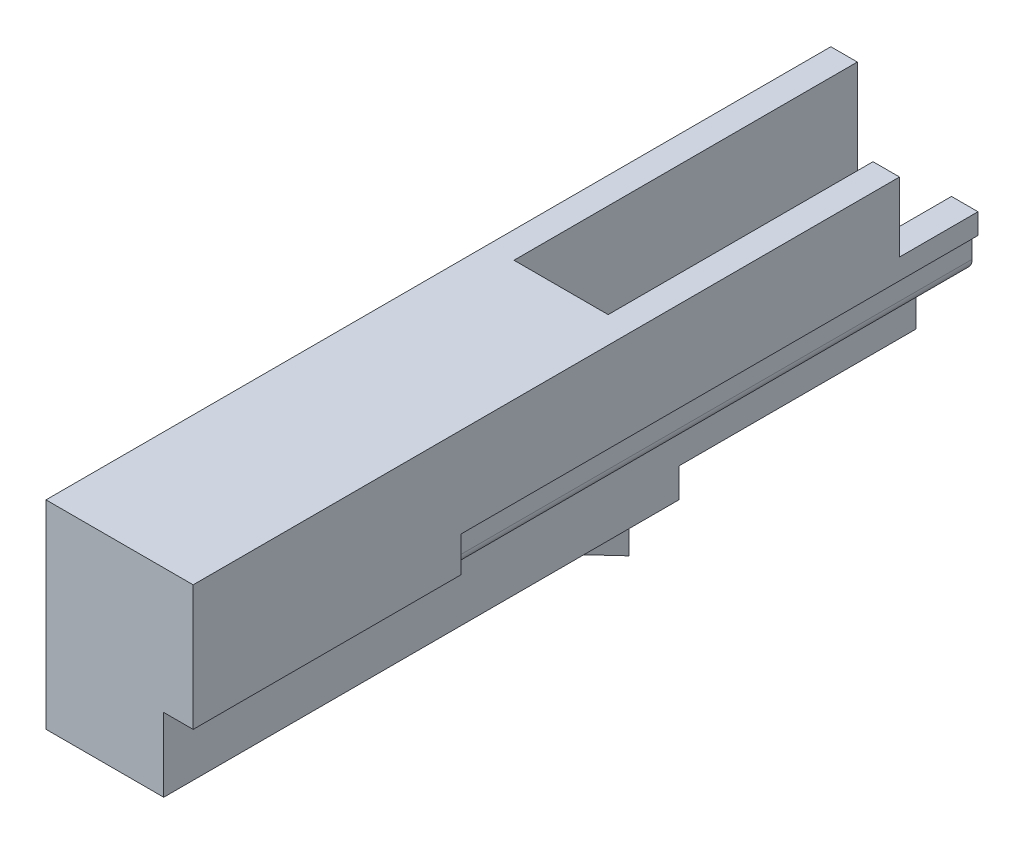
SolidWorks part; units mm, degrees
ref_plane "Front Plane" through (0, 0, 0) normal (0, 0, 1) x (1, 0, 0)
ref_plane "Top Plane" through (0, 0, 0) normal (0, 1, 0) x (1, 0, 0)
ref_plane "Right Plane" through (0, 0, 0) normal (1, 0, 0) x (0, 0, -1)
sketch "Sketch1" plane through (0, 0, 0) normal (0, 0, 1) x (1, 0, 0)
  line L0 (0, 0) -> (0, 86.52)
  line L1 (0, 86.52) -> (-50, 86.52)
  line L2 (-50, 86.52) -> (-50, 0)
  line L3 (-50, 0) -> (0, 0)
  dimension "D1" = 50
  dimension "D2" = 86.52
extrude "Boss-Extrude1" add sketch "Sketch1" along normal blind 266.658
sketch "Sketch2" plane through (0, 86.52, 0) normal (0, 1, 0) x (1, 0, 0)
  line L0 (-41, 0) -> (-41, -116.66)
  line L1 (0, 0) -> (-50, 0) construction
  line L2 (-41, -116.66) -> (-9, -116.66)
  line L3 (-9, -116.66) -> (-9, 0)
  line L4 (-9, 0) -> (-41, 0)
  line L5 (-50, -266.658) -> (-50, 0) construction
  dimension "D1" = 32
  dimension "D2" = 9
  dimension "D3" = 116.66
extrude "Cut-Extrude1" cut sketch "Sketch2" against normal blind 39.55
sketch "Sketch3" plane through (0, 46.97, 0) normal (0, 1, 0) x (1, 0, 0)
  line L0 (-41, 0) -> (-41, -11)
  line L1 (-41, 0) -> (-41, -116.66) construction
  line L2 (-41, -11) -> (-9, -11)
  line L3 (-9, -116.66) -> (-9, 0) construction
  line L4 (-9, -11) -> (-9, 0)
  line L5 (-9, 0) -> (-41, 0)
  dimension "D1" = 11
extrude "Cut-Extrude2" cut sketch "Sketch3" against normal through all
sketch "Sketch4" plane through (0, 46.97, 0) normal (0, 1, 0) x (1, 0, 0)
  line L0 (-36.5, -11) -> (-36.5, -44)
  line L1 (-41, -11) -> (-9, -11) construction
  line L2 (-36.5, -44) -> (-13.5, -44)
  line L3 (-13.5, -44) -> (-13.5, -11)
  line L4 (-13.5, -11) -> (-36.5, -11)
  line L5 (-41, -11) -> (-41, -116.66) construction
  dimension "D1" = 4.5
  dimension "D2" = 23
  dimension "D3" = 33
extrude "Cut-Extrude3" cut sketch "Sketch4" against normal through all
sketch "Sketch5" plane through (0, 46.97, 0) normal (0, 1, 0) x (1, 0, 0)
  line L0 (-34.5, -44) -> (-34.5, -96)
  line L1 (-36.5, -44) -> (-13.5, -44) construction
  line L2 (-34.5, -96) -> (-15.5, -96)
  line L3 (-15.5, -96) -> (-15.5, -44)
  line L4 (-15.5, -44) -> (-34.5, -44)
  line L5 (-41, -11) -> (-41, -116.66) construction
  dimension "D1" = 6.5
  dimension "D2" = 19
  dimension "D3" = 52
extrude "Cut-Extrude4" cut sketch "Sketch5" against normal through all
sketch "Sketch6" plane through (0, 46.97, 0) normal (0, 1, 0) x (1, 0, 0)
  line L0 (-34.5, -96) -> (-34.5, -99)
  line L1 (-15.5, -96) -> (-15.5, -99)
  line L2 (-15.5, -99) -> (-34.5, -99)
  line L3 (-34.5, -96) -> (-15.5, -96)
  dimension "D1" = 3
extrude "Cut-Extrude5" cut sketch "Sketch6" against normal blind 3
sketch "Sketch7" plane through (0, 0, 0) normal (1, 0, 0) x (0, 0, -1)
  line L0 (0, 62.97) -> (-26.66, 62.97)
  line L1 (0, 0) -> (0, 86.52) construction
  line L2 (-26.66, 62.97) -> (-26.66, 86.52)
  line L3 (-266.658, 86.52) -> (0, 86.52) construction
  line L4 (-26.66, 86.52) -> (0, 86.52)
  line L5 (0, 86.52) -> (0, 62.97)
  dimension "D1" = 26.66
  dimension "D2" = 23.55
extrude "Cut-Extrude6" cut sketch "Sketch7" against normal blind 11
sketch "Sketch8" plane through (0, 0, 0) normal (1, 0, 0) x (0, 0, -1)
  line L0 (-96.66, 0) -> (-96.66, 18.97)
  line L1 (-266.658, 0) -> (0, 0) construction
  line L2 (-96.66, 18.97) -> (0, 18.97)
  line L3 (0, 0) -> (0, 62.97) construction
  line L4 (0, 18.97) -> (0, 0)
  line L5 (0, 0) -> (-96.66, 0)
  line L6 (-266.658, 86.52) -> (-26.66, 86.52) construction
  dimension "D1" = 96.66
  dimension "D2" = 67.55
extrude "Cut-Extrude7" cut sketch "Sketch8" against normal through all
sketch "Sketch9" plane through (0, 0, 0) normal (1, 0, 0) x (0, 0, -1)
  line L0 (-91.656, 18.97) -> (-91.656, 28.97)
  line L1 (0, 18.97) -> (-96.66, 18.97) construction
  line L2 (-91.656, 28.97) -> (-11, 28.97)
  line L3 (-11, 28.97) -> (-11, 18.97)
  line L4 (-11, 18.97) -> (-91.656, 18.97)
  line L5 (0, 18.97) -> (0, 62.97) construction
  line L6 (-266.658, 86.52) -> (-26.66, 86.52) construction
  dimension "D1" = 11
  dimension "D2" = 91.656
  dimension "D3" = 57.55
extrude "Cut-Extrude8" cut sketch "Sketch9" against normal through all
sketch "Sketch10" plane through (0, 0, 0) normal (1, 0, 0) x (0, 0, -1)
  line L0 (-11, 18.97) -> (-11, 43.97)
  line L1 (-11, 43.97) -> (0, 43.97)
  line L2 (0, 18.97) -> (0, 62.97) construction
  line L3 (0, 43.97) -> (0, 18.97)
  line L4 (0, 18.97) -> (-11, 18.97)
  line L5 (-266.658, 86.52) -> (-26.66, 86.52) construction
  dimension "D1" = 42.55
extrude "Cut-Extrude9" cut sketch "Sketch10" against normal through all
sketch "Sketch11" plane through (0, 0, 0) normal (1, 0, 0) x (0, 0, -1)
  line L0 (0, 55.97) -> (-175.66, 55.97)
  line L1 (0, 43.97) -> (0, 62.97) construction
  line L2 (-175.66, 55.97) -> (-175.66, 0)
  line L3 (-266.658, 0) -> (-96.66, 0) construction
  line L4 (0, 55.97) -> (0, 0)
  line L5 (0, 0) -> (-175.66, 0)
  line L6 (-266.658, 86.52) -> (-26.66, 86.52) construction
  dimension "D1" = 30.55
  dimension "D2" = 175.66
extrude "Cut-Extrude10" cut sketch "Sketch11" against normal blind 2
sketch "Sketch12" plane through (0, 0, 0) normal (1, 0, 0) x (0, 0, -1)
  line L0 (-266.658, 43.97) -> (0, 43.97)
  line L1 (-266.658, 0) -> (-266.658, 86.52) construction
  line L2 (0, 55.97) -> (-175.66, 55.97) construction
  line L3 (-266.658, 43.97) -> (-266.658, -15.4484)
  line L4 (-266.658, -15.4484) -> (0, -15.4484)
  line L5 (0, -15.4484) -> (0, 43.97)
  dimension "D1" = 12
extrude "Cut-Extrude11" cut sketch "Sketch12" against normal blind 10
fillet "Fillet2" radius 4 1 edges at (-2, 43.97, 87.83)
sketch "Sketch13" plane through (0, 0, 96) normal (0, 0, -1) x (-1, 0, 0)
  line L0 (15.5, 39.97) -> (34.5, 39.97)
  line L1 (15.5, 18.97) -> (15.5, 43.97) construction
  line L2 (34.5, 18.97) -> (34.5, 43.97) construction
  line L3 (34.5, 39.97) -> (34.5, -8.1474)
  line L4 (34.5, -8.1474) -> (15.5, -8.1474)
  line L5 (15.5, -8.1474) -> (15.5, 39.97)
  line L6 (15.5, 43.97) -> (34.5, 43.97) construction
  dimension "D1" = 4
extrude "Cut-Extrude12" cut sketch "Sketch13" against normal blind 2.659
sketch "Sketch16" plane through (0, 0, 98.659) normal (0, 0, -1) x (-1, 0, 0)
  line L0 (15.5, 39.97) -> (34.5, 39.97)
  line L1 (34.5, 39.97) -> (34.5, 16.938)
  line L2 (34.5, 0) -> (34.5, 39.97) construction
  line L3 (34.5, 16.938) -> (15.5, 16.938)
  line L4 (15.5, 39.97) -> (15.5, 0) construction
  line L5 (15.5, 16.938) -> (15.5, 39.97)
  dimension "D1" = 23.032
extrude "Cut-Extrude13" cut sketch "Sketch16" against normal blind 0.341
sketch "Sketch18" plane through (-10, 0, 0) normal (1, 0, 0) x (0, 0, -1)
  line L2 (-133.131, 19) -> (-96.66, 0)
  line L4 (-133.131, 19) -> (-266.658, 19)
  line L5 (-266.658, 43.97) -> (-266.658, 0) construction
  line L6 (-266.658, 19) -> (-266.658, 0)
  line L7 (-266.658, 0) -> (-96.66, 0)
  dimension "D1" = 19
  dimension "D2" = 36.471
extrude "Cut-Extrude14" cut sketch "Sketch18" against normal through all
sketch "Sketch19" plane through (-10, 0, 0) normal (1, 0, 0) x (0, 0, -1)
  line L2 (-96.66, 0) -> (-133.131, 19)
  line L3 (-96.66, 19) -> (-96.66, 0)
  line L4 (-96.66, 0) -> (-96.66, 18.97) construction
  line L5 (-96.66, 19) -> (-133.131, 19)
extrude "Cut-Extrude15" cut sketch "Sketch19" against normal blind 10
sketch "Sketch22" plane through (0, 18.97, 0) normal (0, -1, 0) x (1, 0, 0)
  line L0 (-10, 96.66) -> (-10, 91.656)
  line L1 (-10, 91.656) -> (-15.5, 91.656)
  line L2 (-15.5, 91.656) -> (-15.5, 96.66) construction
  line L3 (-15.5, 91.656) -> (-10, 91.656) construction
  line L4 (-15.5, 91.656) -> (-15.5, 96.66)
  line L5 (-15.5, 96.66) -> (-10, 96.66)
extrude "Cut-Extrude16" cut sketch "Sketch22" against normal blind 0.03
sketch "Sketch24" plane through (0, 19, 0) normal (0, -1, 0) x (1, 0, 0)
  line L0 (-20, 99) -> (-20, 184.4868)
  line L1 (-20, 184.4868) -> (-15.5, 184.4868)
  line L2 (-15.5, 184.4868) -> (-15.5, 99)
  line L3 (-15.5, 99) -> (-20, 99)
  point P4 (-15.5, 141.7434)
  dimension "D1" = 4.5
extrude "Boss-Extrude2" add sketch "Sketch24" along normal blind 0.03
